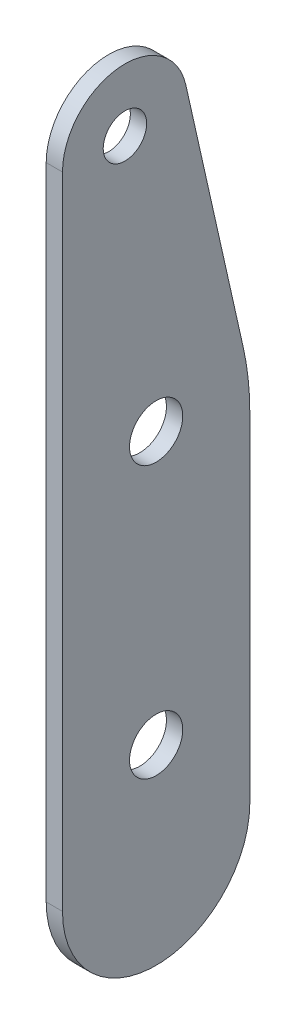
SolidWorks part; units mm, degrees
material "ABS PC"
ref_plane "Front Plane" through (0, 0, 0) normal (0, 0, 1) x (1, 0, 0)
ref_plane "Top Plane" through (0, 0, 0) normal (0, 1, 0) x (1, 0, 0)
ref_plane "Right Plane" through (0, 0, 0) normal (1, 0, 0) x (0, 0, -1)
sketch "Sketch1" plane through (0, 0, 0) normal (1, 0, 0) x (0, 0, -1)
  line L0 (9.525, -1.4499) -> (9.525, -36.83) construction
  line L1 (9.525, -36.83) -> (13.97, -36.83) construction
  line L2 (13.97, -36.83) -> (13.97, -41.91) construction
  line L3 (13.97, -41.91) -> (-11.7668, -67.6468) construction
  line L4 (8.763, -34.507) -> (8.763, 0)
  line L5 (-8.763, -34.507) -> (-8.763, 25.4)
  line L6 (2.7794, 26.6785) -> (8.763, 0)
  circle A0 centre (0, 0) radius 2.4892
  circle A1 centre (0, -25.4) radius 2.4892
  arc A2 (8.763, -34.507) -> (-8.763, -34.507) centre (0, -34.507) cw
  circle A3 centre (-2.921, 25.4) radius 2.032
  arc A4 (-8.763, 25.4) -> (2.7794, 26.6785) centre (-2.921, 25.4) cw
  dimension "D1" = 25.4
  dimension "D2" = 4.9784
  dimension "D8" = 6.35
  dimension "D10" = 4.064
  dimension "D11" = 3.81
  dimension "D3" = 4.445
  dimension "D4" = 13.97
  dimension "D5" = 36.83
  dimension "D6" = 5.08
  dimension "D7" = 45
  dimension "D9" = 8.763
  dimension "D12" = 25.4
extrude "Boss-Extrude1" add sketch "Sketch1" along normal blind 1.524
fillet "Fillet1" radius 25.4 1 edges at (0.762, 0, -8.763)
sketch "Sketch2" plane through (0, 0, 0) normal (-1, 0, 0) x (0, 0, 1)
  line L10 (44.6718, -23.9147) -> (35.5018, -23.9147)
  line L11 (44.6718, -23.9147) -> (44.6718, -14.9502)
  line L12 (35.5018, -23.9147) -> (35.5018, -14.9502)
  line L13 (44.6718, -14.9502) -> (35.5018, -14.9502)
extrude "Boss-Extrude2" [suppressed] add sketch "Sketch2" against normal up to surface (1.524 mm away)
sketch "Sketch3" [suppressed] plane through (0, 0, 0) normal (-1, 0, 0) x (0, 0, 1)
  line L0 (8.763, 25.4) -> (8.763, -34.507) construction
  line L1 (8.763, 17.1427) -> (24.8425, 17.1427)
  line L2 (8.763, 17.1427) -> (8.763, 1.9027)
  line L3 (8.763, 1.9027) -> (24.8425, 1.9027)
  line L4 (24.8425, 17.1427) -> (24.8425, 1.9027)
  line L5 (-8.763, -34.507) -> (-8.763, -2.8135) construction
  line L6 (-8.763, -10.8935) -> (-29.213, -10.8935)
  line L7 (-8.763, -10.8935) -> (-8.763, -26.1335)
  line L8 (-8.763, -26.1335) -> (-29.213, -26.1335)
  line L9 (-29.213, -10.8935) -> (-29.213, -26.1335)
  dimension "D1" = 15.24
extrude "Boss-Extrude3" [suppressed] add sketch "Sketch3" against normal up to surface (1.524 mm away)
